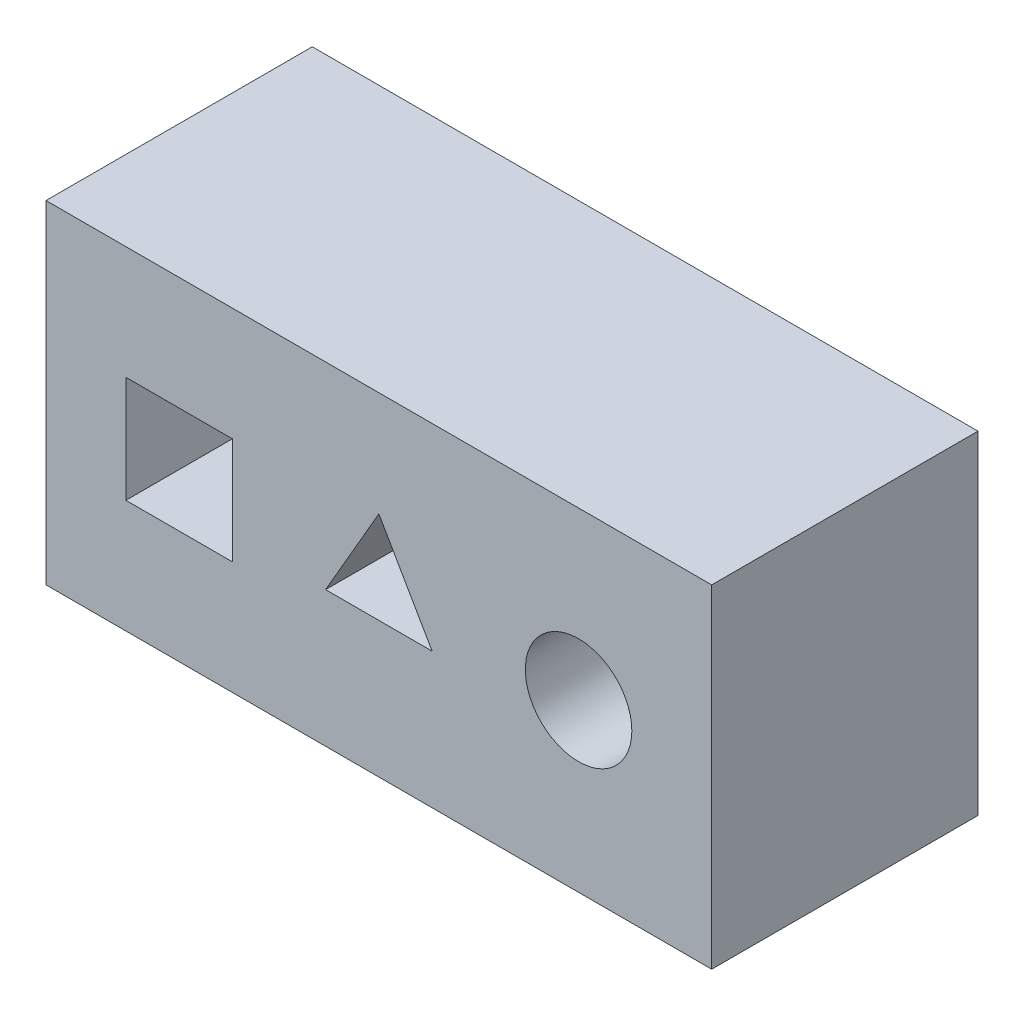
SolidWorks part; units mm, degrees
ref_plane "Front Plane" through (0, 0, 0) normal (0, 0, 1) x (1, 0, 0)
ref_plane "Top Plane" through (0, 0, 0) normal (0, 1, 0) x (1, 0, 0)
ref_plane "Right Plane" through (0, 0, 0) normal (1, 0, 0) x (0, 0, -1)
sketch "Sketch1" plane through (0, 0, 0) normal (0, 0, 1) x (1, 0, 0)
  line L1 (125, -62.5) -> (-125, -62.5)
  line L2 (125, -62.5) -> (125, 62.5)
  line L3 (125, 62.5) -> (-125, 62.5)
  line L4 (-125, -62.5) -> (-125, 62.5)
  line L5 (125, -62.5) -> (-125, 62.5) construction
  line L6 (125, 62.5) -> (-125, -62.5) construction
  line L7 (115, -57.5) -> (-115, -57.5)
  line L8 (115, -57.5) -> (115, 57.5)
  line L9 (115, 57.5) -> (-115, 57.5)
  line L10 (-115, -57.5) -> (-115, 57.5)
  line L11 (115, -57.5) -> (-115, 57.5) construction
  line L12 (115, 57.5) -> (-115, -57.5) construction
  point P0 (0, 0)
  point P6 (0, 0)
  dimension "D1" = 250
  dimension "D2" = 125
  dimension "D3" = 230
extrude "Boss-Extrude1" add sketch "Sketch1" along normal blind 100
sketch "Sketch2" plane through (0, 0, 0) normal (0, 0, -1) x (-1, 0, 0)
  line L1 (125, 62.5) -> (-125, 62.5)
  line L2 (125, 62.5) -> (125, -62.5)
  line L3 (125, -62.5) -> (-125, -62.5)
  line L4 (-125, 62.5) -> (-125, -62.5)
sketch "Sketch3" plane through (0, 0, 100) normal (0, 0, 1) x (1, 0, 0)
  line L0 (-125, 0) -> (125, 0) construction
  line L1 (-125, 62.5) -> (125, 62.5)
  line L2 (-125, 62.5) -> (-125, -62.5)
  line L3 (-125, -62.5) -> (125, -62.5)
  line L4 (125, 62.5) -> (125, -62.5)
  line L5 (0, 62.5) -> (0, -62.5) construction
  line L6 (-20, -11.547) -> (0, 23.094)
  line L7 (-95, 20) -> (-55, 20)
  line L8 (-95, 20) -> (-95, -20)
  line L9 (-95, -20) -> (-55, -20)
  line L10 (-55, 20) -> (-55, -20)
  line L11 (-95, 20) -> (-55, -20) construction
  line L12 (-95, -20) -> (-55, 20) construction
  line L14 (-1.3522, 0) -> (0, -1.3522)
  line L18 (0, 23.094) -> (20, -11.547)
  line L19 (20, -11.547) -> (-20, -11.547)
  line L20 (-20, -11.547) -> (10, 5.7735) construction
  line L21 (20, -11.547) -> (-10, 5.7735) construction
  line L22 (0, 23.094) -> (0, 0) construction
  circle A0 centre (75, 0) radius 20
  point P10 (-75, 0)
  point P20 (0, 0)
  point P27 (7.7505, -5.3087)
  point P28 (0, 0)
  line M21 (-125, 62.5) -> (-125, -62.5)
  line M22 (-125, -62.5) -> (125, -62.5)
  line M23 (125, -62.5) -> (125, 62.5)
  line M24 (125, 62.5) -> (-125, 62.5)
  line M25 (115, -57.5) -> (-115, -57.5)
  line M26 (-115, -57.5) -> (-115, 57.5)
  line M27 (-115, 57.5) -> (115, 57.5)
  line M28 (115, 57.5) -> (115, -57.5)
  dimension "D2" = 50
  dimension "cylinder" = 40
  dimension "D1" = 30
  dimension "square2" = 40
  dimension "square" = 40
  dimension "triangle3" = 40
  dimension "triangle2" = 40
  dimension "triangle" = 40
extrude "Boss-Extrude4" add sketch "Sketch3" against normal up to surface (100 mm away) contours A0 L7 L10 L9 L8 L18 L19 L6 M25 M28 M27 M26 | M24 M21 M22 M23 M28 M25 M26 M27 up to face at (0, 0, 0)
